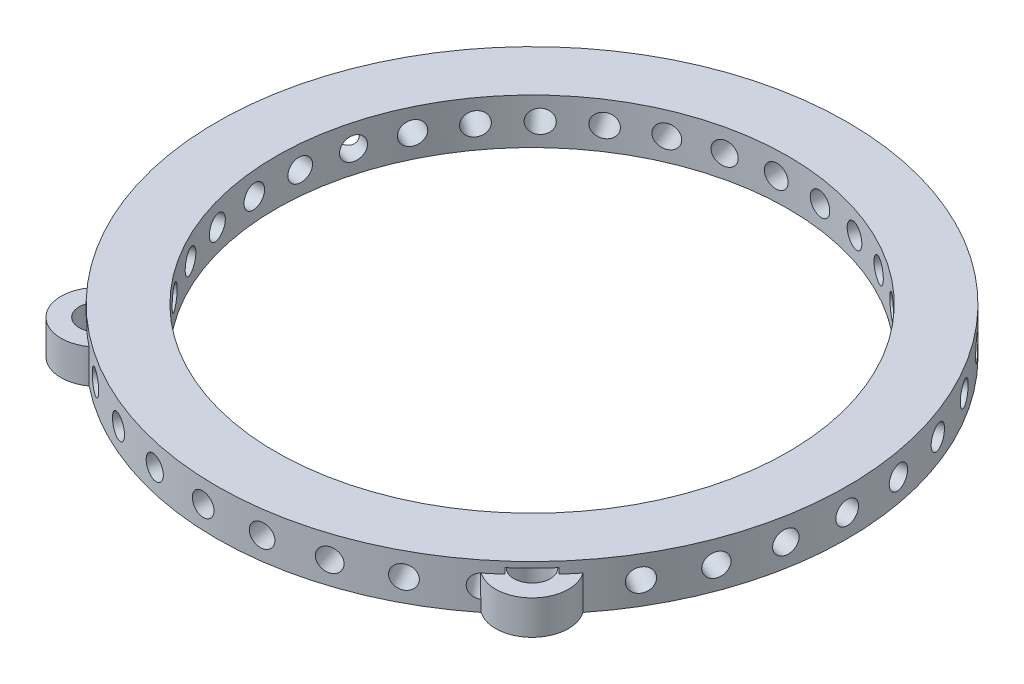
SolidWorks part; units mm, degrees
material "ABS"
ref_plane "Alzado" through (0, 0, 0) normal (0, 0, 1) x (1, 0, 0)
ref_plane "Planta" through (0, 0, 0) normal (0, 1, 0) x (1, 0, 0)
ref_plane "Vista lateral" through (0, 0, 0) normal (1, 0, 0) x (0, 0, -1)
sketch "Croquis2" plane through (0, 0, 0) normal (0, 0, 1) x (1, 0, 0)
  line L0 (0, 0) -> (-22.5, 0) construction
  line L1 (-22.5, 0) -> (-22.5, 1)
  line L2 (-22.5, 1) -> (-22.5, 4)
  line L3 (-22.5, 0) -> (-27.7, 0)
  line L4 (-27.7, 0) -> (-27.7, 4)
  line L5 (-27.7, 4) -> (-22.5, 4)
  line L6 (0, 0) -> (0, 4.6512) construction
  dimension "D1" = 22.5
  dimension "D2" = 1
  dimension "D3" = 3
  dimension "D4" = 27.7
revolve "Revolución1" add sketch "Croquis2" angle 360 about L6
ref_plane "Plano1" through (27.7, 0, 0) normal (1, 0, 0) x (0, 0, -1)
sketch "Croquis3" plane through (27.7, 0, 0) normal (1, 0, 0) x (0, 0, -1)
  circle A0 centre (0, 2) radius 1
  point P4 (0, 0)
  dimension "D1" = 2
  dimension "D2" = 2
ref_plane "Plano2" through (0, 0, 0) normal (0, 0, -1) x (-1, 0, 0)
sketch "Croquis4" plane through (0, 0, 0) normal (0, 0, -1) x (-1, 0, 0)
  line L0 (-27.7, 2) -> (-24.2359, 0) construction
  line L1 (-24.2359, 0) -> (-27.7, 0) construction
  dimension "D1" = 30
extrude "Cortar-Extruir1" cut sketch "Croquis3" against normal up to surface (5.2222 mm away)
pattern_circular "MatrizC1" count 35 over 360 about axis through (0, 0, 0) along (0, -1, 0) of "Cortar-Extruir1"
sketch "Croquis5" plane through (0, 0, 0) normal (0, -1, 0) x (1, 0, 0)
  line L0 (0, 0) -> (-19.0919, 19.0919) construction
  line L2 (0, 0) -> (0, -25.1) construction
  line L3 (0, 0) -> (-23.5863, -8.5847) construction
  circle A2 centre (0, -25.1) radius 1.8
  circle A6 centre (0, 0) radius 25.1 construction
  circle A9 centre (-23.5863, -8.5847) radius 1.8
  circle A10 centre (-19.0919, 19.0919) radius 1.8
  circle A11 centre (19.0919, 19.0919) radius 1.8
  circle A12 centre (23.5863, -8.5847) radius 1.8
  point P18 (0, 0)
  dimension "D1" = 3.6
  dimension "D2" = 50.2
  dimension "D4" = 3.6
  dimension "D7" = 3.6
  dimension "D3" = 70
  dimension "D5" = 27
  dimension "D6" = 135
extrude "Cortar-Extruir2" cut sketch "Croquis5" against normal blind 3.5
sketch "Croquis6" plane through (0, 0, 0) normal (0, -1, 0) x (1, 0, 0)
  line L0 (0, 0) -> (0, -22.5) construction
  line L1 (-19.0919, 20.6919) -> (-19.0919, 22.2919) construction
  circle A0 centre (-19.0919, 19.0919) radius 1.6
  circle A2 centre (0, 0) radius 22.5 construction
  circle A3 centre (19.0919, 19.0919) radius 1.6
  circle A5 centre (0, 0) radius 30.2 construction
  circle A6 centre (-19.0919, 19.0919) radius 3.2
  circle A7 centre (19.0919, 19.0919) radius 3.2
  dimension "D1" = 1.6
  dimension "D2" = 3.2
extrude "Saliente-Extruir1" add sketch "Croquis6" against normal blind 3
